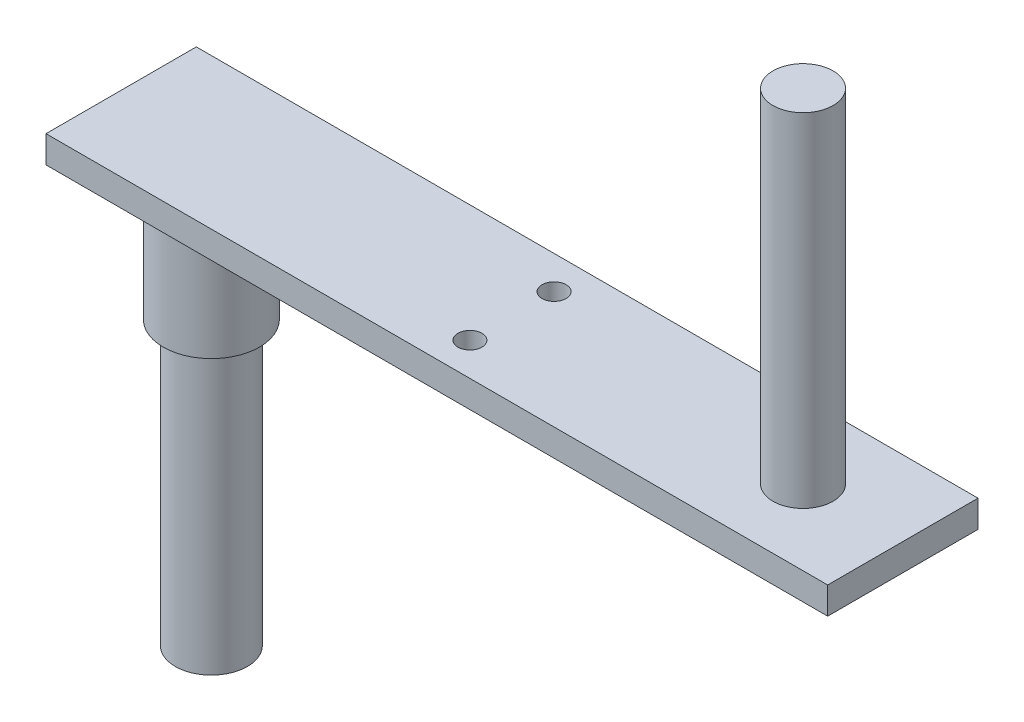
SolidWorks part; units mm, degrees
ref_plane "Спереди" through (0, 0, 0) normal (0, 0, 1) x (1, 0, 0)
ref_plane "Сверху" through (0, 0, 0) normal (0, 1, 0) x (1, 0, 0)
ref_plane "Справа" through (0, 0, 0) normal (1, 0, 0) x (0, 0, -1)
sketch "Эскиз1" plane through (0, 0, 0) normal (0, 1, 0) x (1, 0, 0)
  line L1 (-65, -12.5) -> (65, -12.5)
  line L2 (-65, -12.5) -> (-65, 12.5)
  line L3 (-65, 12.5) -> (65, 12.5)
  line L4 (65, -12.5) -> (65, 12.5)
  line L5 (-65, -12.5) -> (65, 12.5) construction
  line L6 (-65, 12.5) -> (65, -12.5) construction
  point P0 (0, 0)
  dimension "D1" = 130
  dimension "D2" = 25
extrude "Бобышка-Вытянуть1" add sketch "Эскиз1" along normal blind 4.5
sketch "Эскиз2" plane through (0, 4.5, 0) normal (0, 1, 0) x (1, 0, 0)
  line L0 (65, -12.5) -> (65, 12.5) construction
  circle A0 centre (48.4, 0) radius 5
  point P5 (65, 0)
  dimension "D1" = 10
  dimension "D2" = 11.6
extrude "Бобышка-Вытянуть2" add sketch "Эскиз2" along normal blind 57
sketch "Эскиз3" plane through (0, 0, 0) normal (0, -1, 0) x (1, 0, 0)
  line L0 (-65, -12.5) -> (-65, 12.5) construction
  circle A0 centre (-50, 0) radius 8
  point P4 (-65, 0)
  dimension "D1" = 16
  dimension "D2" = 15
extrude "Бобышка-Вытянуть3" add sketch "Эскиз3" along normal blind 21
sketch "Эскиз4" plane through (0, -21, 0) normal (0, -1, 0) x (1, 0, 0)
  circle A0 centre (-50, 0) radius 6
  dimension "D1" = 12
extrude "Бобышка-Вытянуть4" add sketch "Эскиз4" along normal blind 47
sketch "Эскиз5" plane through (0, 0, 0) normal (0, -1, 0) x (1, 0, 0)
  line L0 (0, 0) -> (19.9979, 0) construction
  circle A0 centre (0, 7) radius 2
  circle A1 centre (0, -7) radius 2
  dimension "D1" = 14
  dimension "D2" = 4
extrude "Вырез-Вытянуть1" cut sketch "Эскиз5" against normal up to next
